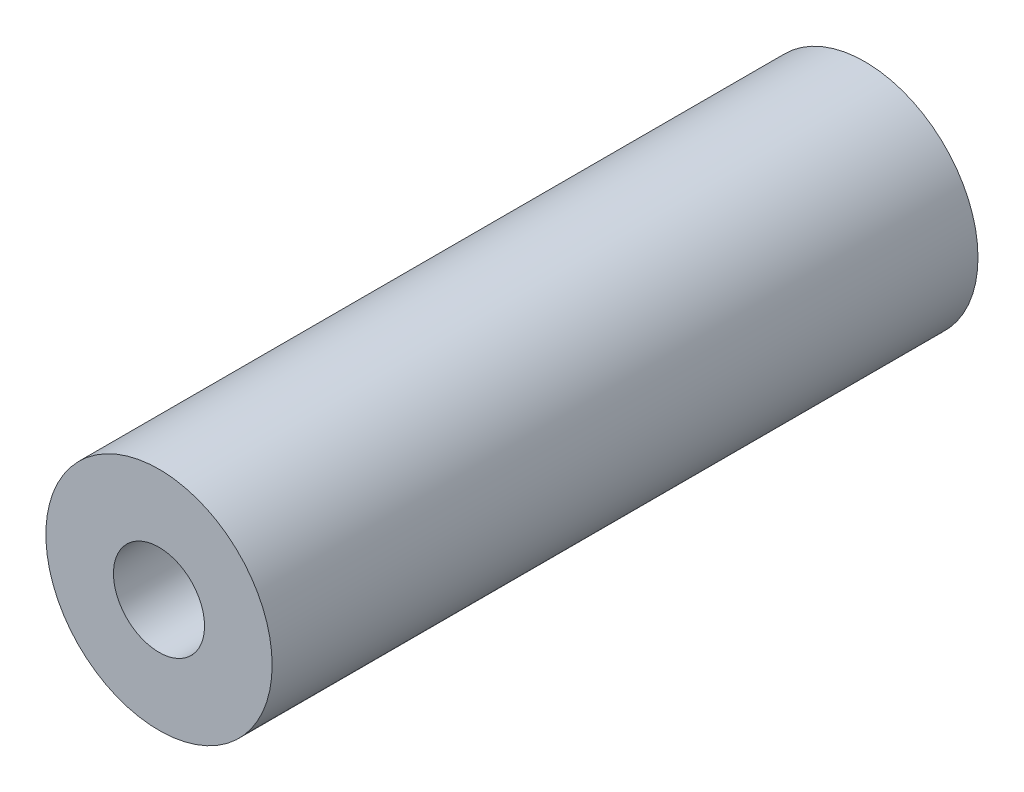
SolidWorks part; units mm, degrees
material "SBR"
ref_plane "Front Plane" through (0, 0, 0) normal (0, 0, 1) x (1, 0, 0)
ref_plane "Top Plane" through (0, 0, 0) normal (0, 1, 0) x (1, 0, 0)
ref_plane "Right Plane" through (0, 0, 0) normal (1, 0, 0) x (0, 0, -1)
sketch "Sketch1" plane through (0, 0, 0) normal (0, 0, 1) x (1, 0, 0)
  circle A0 centre (0, 0) radius 31.5532
  circle A1 centre (0, 0) radius 12.7
  dimension "D1" = 25.4
  dimension "D2" = 63.1063
extrude "Boss-Extrude1" add sketch "Sketch1" along normal blind 196.85 contours A0
